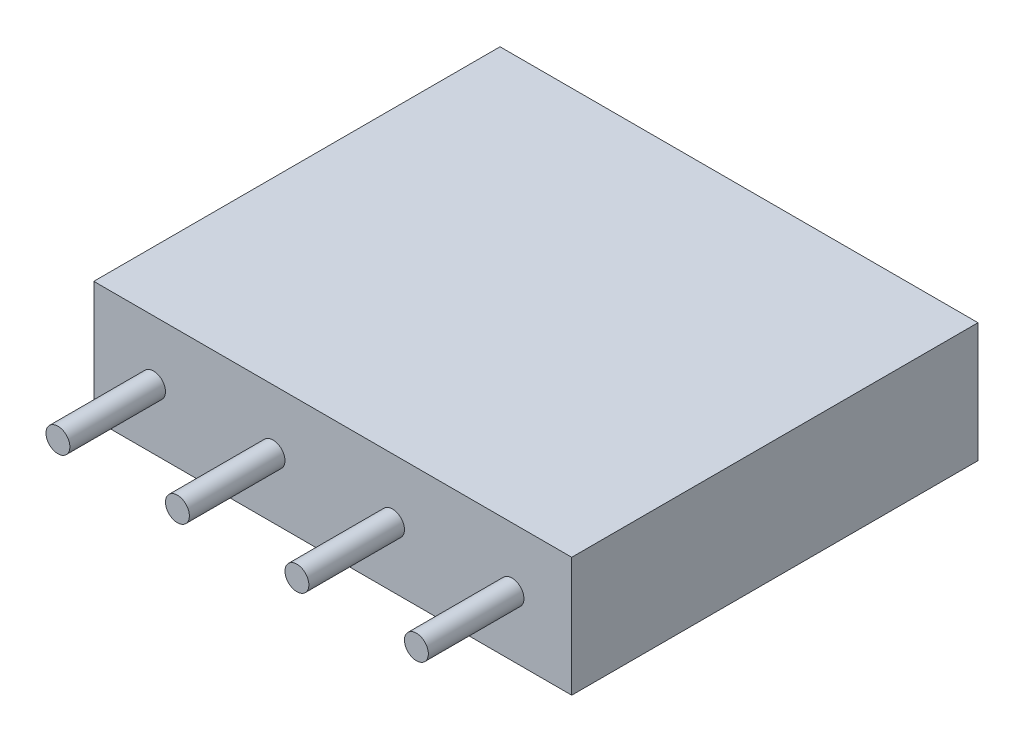
SolidWorks part; units mm, degrees
ref_plane "Plan de face" through (0, 0, 0) normal (0, 0, 1) x (1, 0, 0)
ref_plane "Plan de dessus" through (0, 0, 0) normal (0, 1, 0) x (1, 0, 0)
ref_plane "Plan de droite" through (0, 0, 0) normal (1, 0, 0) x (0, 0, -1)
sketch "Esquisse1" plane through (0, 0, 0) normal (0, 0, 1) x (1, 0, 0)
  line L1 (0, 0) -> (-2.5, 0)
  line L2 (0, 0) -> (0, 2.5)
  line L3 (0, 2.5) -> (-2.5, 2.5)
  line L4 (-2.5, 0) -> (-2.5, 2.5)
  dimension "D1" = 2.5
  dimension "D2" = 2.5
extrude "Boss.-Extru.1" add sketch "Esquisse1" along normal blind 8.5
sketch "Esquisse2" plane through (0, 0, 8.5) normal (0, 0, 1) x (1, 0, 0)
  line L0 (-2.5, 2.5) -> (0, 0) construction
  circle A0 centre (-1.25, 1.25) radius 0.25
  dimension "D1" = 0.5
extrude "Boss.-Extru.2" add sketch "Esquisse2" along normal blind 2
sketch "Esquisse3" plane through (0, 0, 0) normal (0, 0, -1) x (-1, 0, 0)
  line L0 (0, 2.5) -> (2.5, 0) construction
  circle A0 centre (1.25, 1.25) radius 0.25
  dimension "D1" = 0.5
extrude "Enlèv. mat.-Extru.2" cut sketch "Esquisse3" against normal blind 4
pattern_linear "Répétition linéaire1" count 4 spacing 2.5 along (-1, 0, 0) of "Boss.-Extru.1", "Enlèv. mat.-Extru.2", "Boss.-Extru.2"
